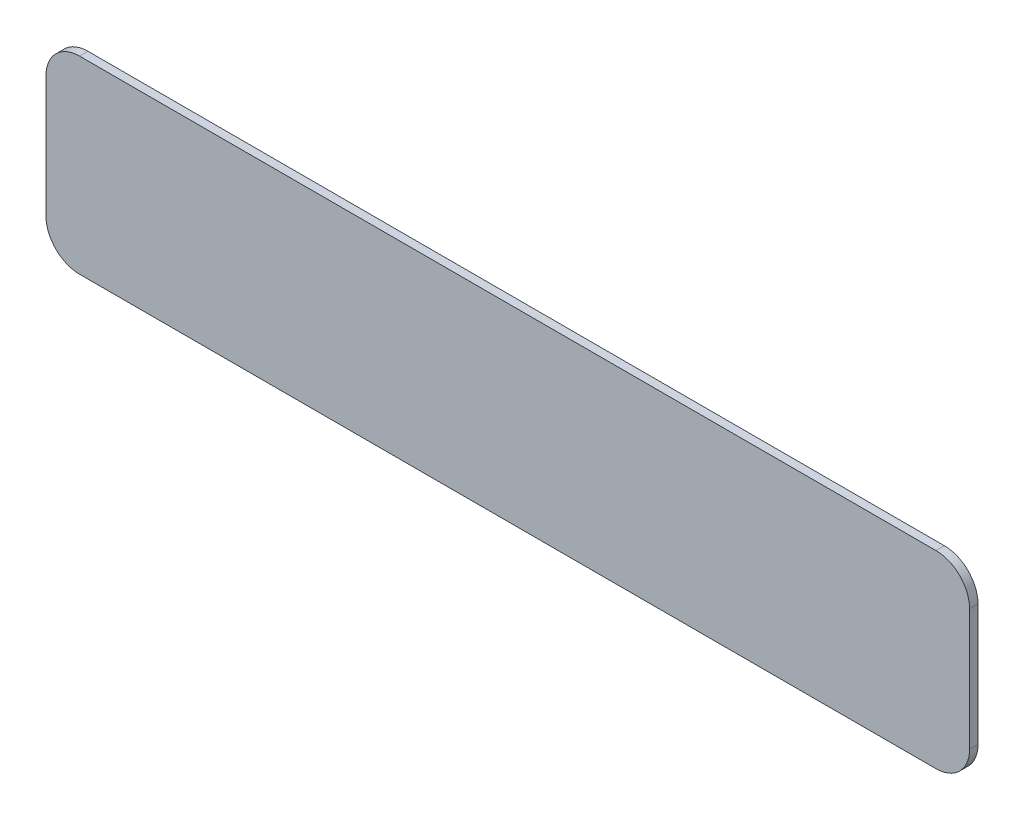
SolidWorks part; units mm, degrees
material "Glass"
ref_plane "Front Plane" through (0, 0, 0) normal (0, 0, 1) x (1, 0, 0)
ref_plane "Top Plane" through (0, 0, 0) normal (0, 1, 0) x (1, 0, 0)
ref_plane "Right Plane" through (0, 0, 0) normal (1, 0, 0) x (0, 0, -1)
sketch "Sketch1" plane through (0, 0, 0) normal (0, 0, 1) x (1, 0, 0)
  line L1 (-51, 11.25) -> (51, 11.25)
  line L2 (-55, 7.25) -> (-55, -7.25)
  line L3 (-51, -11.25) -> (51, -11.25)
  line L4 (55, 7.25) -> (55, -7.25)
  line L5 (-55, 11.25) -> (55, -11.25) construction
  line L6 (-55, -11.25) -> (55, 11.25) construction
  arc A0 (51, -11.25) -> (55, -7.25) centre (51, -7.25) ccw
  arc A1 (55, 7.25) -> (51, 11.25) centre (51, 7.25) ccw
  arc A2 (-51, -11.25) -> (-55, -7.25) centre (-51, -7.25) cw
  arc A3 (-55, 7.25) -> (-51, 11.25) centre (-51, 7.25) cw
  point P0 (0, 0)
  dimension "D3" = 4
  dimension "D1" = 110
  dimension "D2" = 22.5
extrude "Boss-Extrude1" add sketch "Sketch1" along normal blind 1
